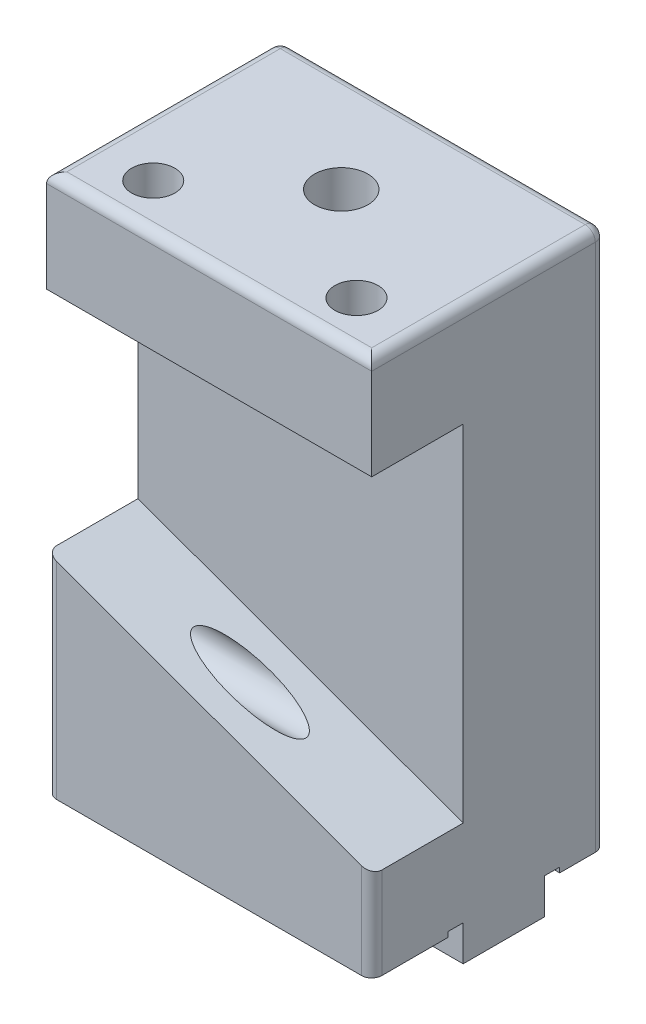
SolidWorks part; units mm, degrees
ref_plane "Front Plane" through (0, 0, 0) normal (0, 0, 1) x (1, 0, 0)
ref_plane "Top Plane" through (0, 0, 0) normal (0, 1, 0) x (1, 0, 0)
ref_plane "Right Plane" through (0, 0, 0) normal (1, 0, 0) x (0, 0, -1)
sketch "Sketch4" plane through (0, 0, 0) normal (0, 0, 1) x (1, 0, 0)
  line L1 (-119.3708, 207.3258) -> (-55.3708, 207.3258)
  line L2 (-119.3708, 207.3258) -> (-119.3708, 95.3258)
  line L3 (-119.3708, 95.3258) -> (-55.3708, 95.3258)
  line L4 (-55.3708, 207.3258) -> (-55.3708, 95.3258)
  line L5 (-119.3708, 207.3258) -> (-55.3708, 95.3258) construction
  line L6 (-119.3708, 95.3258) -> (-55.3708, 207.3258) construction
  point P0 (-87.3708, 151.3258)
  dimension "D1" = 112
  dimension "D2" = 64
extrude "Boss-Extrude1" add sketch "Sketch4" along normal blind 46
sketch "Sketch5" plane through (0, 0, 46) normal (0, 0, 1) x (1, 0, 0)
  line L0 (-119.3708, 187.3258) -> (-55.3708, 187.3258)
  line L1 (-119.3708, 207.3258) -> (-119.3708, 95.3258) construction
  line L2 (-55.3708, 95.3258) -> (-55.3708, 207.3258) construction
  line L3 (-55.3708, 187.3258) -> (-55.3708, 119.3258)
  line L4 (-55.3708, 119.3258) -> (-119.3708, 142.6199)
  line L5 (-119.3708, 142.6199) -> (-119.3708, 187.3258)
  dimension "D1" = 64
  dimension "D2" = 110
  dimension "D3" = 20
  dimension "D4" = 24
extrude "Cut-Extrude1" cut sketch "Sketch5" against normal blind 18
sketch "Sketch6" plane through (-55.3708, 0, 0) normal (1, 0, 0) x (0, 0, -1)
  line L0 (-46, 101.3258) -> (-31, 101.3258)
  line L1 (-46, 95.3258) -> (-46, 119.3258) construction
  line L2 (-31, 101.3258) -> (-31, 102.3258)
  line L3 (-31, 102.3258) -> (-28, 102.3258)
  line L4 (-28, 102.3258) -> (-28, 95.3258)
  line L5 (-46, 95.3258) -> (0, 95.3258) construction
  line L6 (-46, 101.3258) -> (-46, 95.3258)
  line L7 (-12, 95.3258) -> (-12, 101.5651)
  line L8 (-12, 101.5651) -> (-12, 102.3258)
  line L9 (-12, 102.3258) -> (-9, 102.3258)
  line L10 (-9, 102.3258) -> (-9, 101.3258)
  line L11 (-9, 101.3258) -> (0, 101.3258)
  line L12 (0, 95.3258) -> (0, 207.3258) construction
  line L13 (-46, 95.3258) -> (-28, 95.3258)
  line L14 (-12, 95.3258) -> (0, 95.3258)
  line L15 (0, 95.3258) -> (0, 101.3258)
  dimension "D1" = 12
  dimension "D2" = 16
  dimension "D3" = 6
  dimension "D4" = 6
  dimension "D5" = 1
  dimension "D6" = 1
  dimension "D7" = 3
  dimension "D8" = 3
extrude "Cut-Extrude2" cut sketch "Sketch6" against normal blind 90
sketch "Sketch7" plane through (0, 207.3258, 0) normal (0, 1, 0) x (1, 0, 0)
  line L0 (-55.3708, 0) -> (-119.3708, 0) construction
  circle A0 centre (-87.3708, -20) radius 5.25
  dimension "D1" = 10.5
  dimension "D2" = 20
extrude "Cut-Extrude3" cut sketch "Sketch7" against normal blind 273
hole_wizard "M10 Tapped Hole2" positions "3DSketch2" profile "Sketch9" tap size "M10" standard "ISO"
sketch3d "3DSketch2"
  line L0 (-119.3708, 207.3258, 37) -> (-55.3708, 207.3258, 37) construction
  line L1 (-119.3708, 207.3258, 46) -> (-119.3708, 207.3258, 0) construction
  line L2 (-55.3708, 207.3258, 46) -> (-55.3708, 207.3258, 0) construction
  line L4 (-55.3708, 207.3258, 46) -> (-119.3708, 207.3258, 46) construction
  line L5 (-87.3708, 207.3258, 46) -> (-87.3708, 207.3258, 31.6667) construction
  point P0 (-107.3708, 207.3258, 37)
  point P2 (-67.3708, 207.3258, 37)
  dimension "D1" = 9
  dimension "D2" = 20
  dimension "D3" = 20
sketch "Sketch9" plane through (-107.3708, 207.3258, 37) normal (1, 0, 0) x (0, 0, 1)
  line L0 (0, 0) -> (0, 52.5537)
  line L1 (0, 52.5537) -> (4.25, 50)
  line L2 (4.25, 50) -> (4.25, 0)
  line L5 (4.25, 0) -> (0, 0)
  line L10 (0, 52.5537) -> (-4.25, 50) construction
  line L11 (0, -6.35) -> (0, 107.95) construction
  dimension "Tap Drill Dia." = 8.5
  dimension "Tap Drill Depth" = 50
  dimension "Drill Angle" = 118
cosmetic thread "Hole Thread3" parameters "D1"=20, "D2"=10
cosmetic thread "Hole Thread4" parameters "D1"=20, "D2"=10
sketch "Sketch10" plane through (-119.3708, 0, 0) normal (-1, 0, 0) x (0, 0, 1)
  line L2 (31, 101.3258) -> (46, 101.3258) construction
  circle A0 centre (37, 131.3258) radius 5
  dimension "D1" = 10
  dimension "D2" = 9
  dimension "D3" = 30
extrude "Cut-Extrude4" cut sketch "Sketch10" against normal blind 6
sketch "Sketch12" plane through (-113.3708, 0, 0) normal (-1, 0, 0) x (0, 0, 1)
  circle A0 centre (37, 131.3258) radius 4
  dimension "D1" = 8
extrude "Cut-Extrude5" cut sketch "Sketch12" against normal blind 50
fillet "Fillet1" radius 2 8 edges at (-55.3708, 110.3258, 46) (-119.3708, 121.9729, 46) (-119.3708, 154.3258, 0) (-87.3708, 207.3258, 0) (-55.3708, 154.3258, 0) (-55.3708, 207.3258, 23) (-87.3708, 207.3258, 46) (-119.3708, 207.3258, 23)
